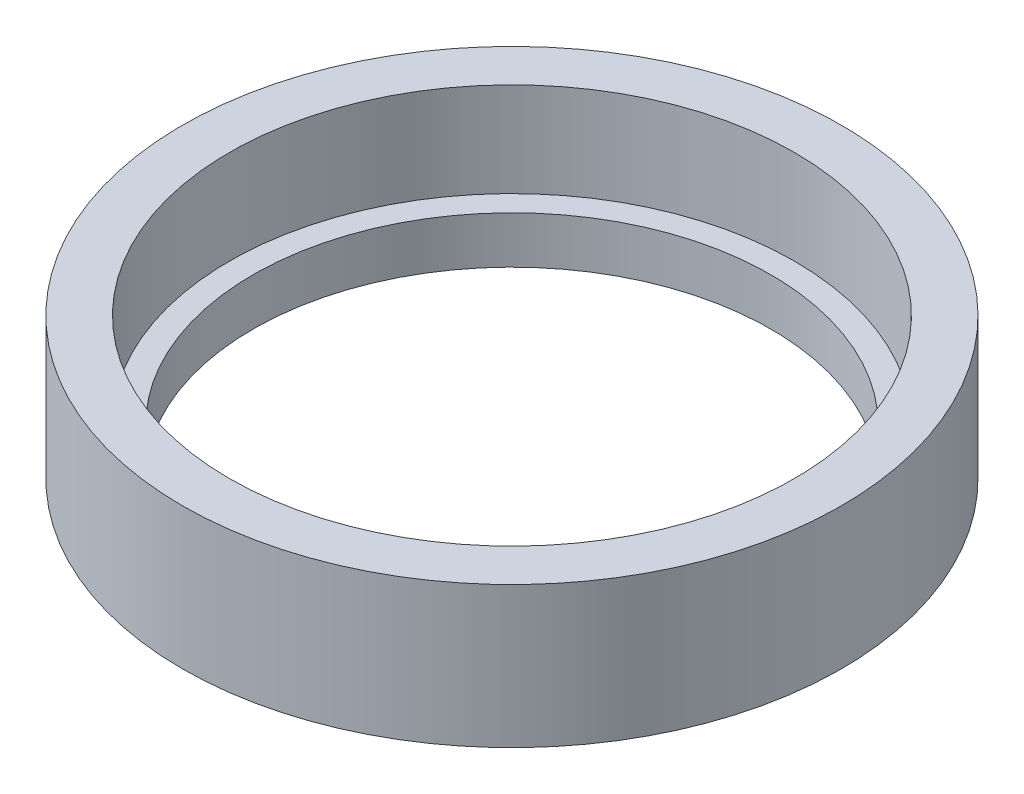
SolidWorks part; units mm, degrees
material "AISI 304"
ref_plane "前视基准面" through (0, 0, 0) normal (0, 0, 1) x (1, 0, 0)
ref_plane "上视基准面" through (0, 0, 0) normal (0, 1, 0) x (1, 0, 0)
ref_plane "右视基准面" through (0, 0, 0) normal (1, 0, 0) x (0, 0, -1)
sketch "Sketch1" plane through (0, 0, 0) normal (0, 1, 0) x (1, 0, 0)
  circle A0 centre (0, 0) radius 27.5
  circle A1 centre (0, 0) radius 35
  dimension "D1" = 70
  dimension "D2" = 55
extrude "Extrude1" add sketch "Sketch1" along normal blind 15
sketch "Sketch3" plane through (0, 15, 0) normal (0, 1, 0) x (1, 0, 0)
  circle A0 centre (0, 0) radius 30
  dimension "D1" = 60
extrude "Extrude3" cut sketch "Sketch3" against normal blind 10
